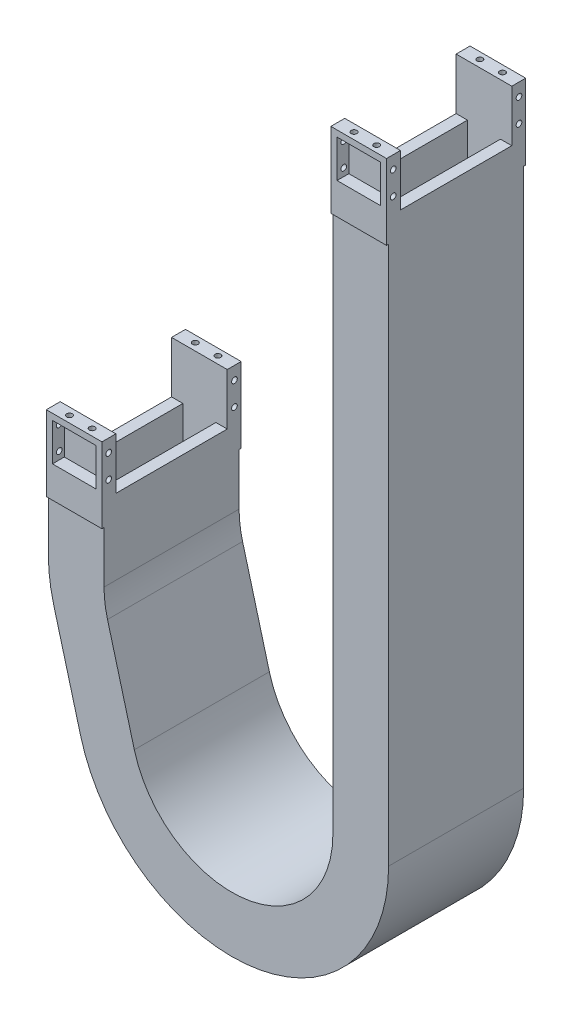
SolidWorks part; units mm, degrees
material "ABS"
ref_plane "Front Plane" through (0, 0, 0) normal (0, 0, 1) x (1, 0, 0)
ref_plane "Top Plane" through (0, 0, 0) normal (0, 1, 0) x (1, 0, 0)
ref_plane "Right Plane" through (0, 0, 0) normal (1, 0, 0) x (0, 0, -1)
ref_plane "Plane1" through (0, 300, 0) normal (0, 1, 0) x (-1, 0, 0)
sketch "Sketch1" plane through (0, 0, 0) normal (0, 0, 1) x (1, 0, 0)
  line L0 (-276, -375) -> (-276, -425)
  line L1 (0, -521.4286) -> (0, 0)
  line L2 (164.2548, 1) -> (-897.999, 1) construction
  line L3 (-245.6899, -553.9702) -> (-271.6899, -457.5416)
  line L4 (164.2548, 1) -> (164.2548, 204.572) construction
  line L5 (164.2548, 204.572) -> (-899.7452, 204.572) construction
  line L6 (164.2548, 204.572) -> (164.2548, 420.7437) construction
  line L7 (164.2548, 420.7437) -> (-507.0461, 420.7437) construction
  line L8 (164.2548, 204.572) -> (183.2548, 204.572) construction
  line L9 (164.2548, 420.7437) -> (164.2548, 572.9286) construction
  line L10 (164.2548, 572.9286) -> (-357.1738, 572.9286) construction
  line L11 (164.2548, 572.9286) -> (164.2548, 662.6262) construction
  line L12 (164.2548, 662.6262) -> (138.2548, 662.6262) construction
  line L13 (164.2548, 662.6262) -> (164.2548, 774.8796) construction
  line L14 (164.2548, 774.8796) -> (360.5557, 774.8796) construction
  arc A0 (-276, -425) -> (-271.6899, -457.5416) centre (-151, -425) ccw
  arc A1 (-245.6899, -553.9702) -> (0, -521.4286) centre (-125, -521.4286) ccw
  point P2 (-275, -99)
  dimension "D4" = 276
  dimension "D1" = 1
  dimension "D13" = 671.3009
  dimension "D6" = 125
  dimension "D2" = 275
  dimension "D3" = 100
  dimension "D5" = 1
  dimension "D7" = 521.4286
  dimension "D8" = 50
  dimension "D9" = 99.8723
  dimension "D10" = 1062.2538
  dimension "D11" = 1064
  dimension "D12" = 19
  dimension "D14" = 521.4286
  dimension "D15" = 26
  dimension "D16" = 196.3009
sketch "Sketch13" plane through (0, 0, 0) normal (0, 0, 1) x (1, 0, 0)
  line L0 (0, 228.6) -> (0, 203.2)
  line L1 (0, 228.6) -> (108, 228.6)
  line L2 (0, 203.2) -> (32, 203.2)
  line L3 (0, 177.8) -> (56, 177.8)
  line L4 (0, 152.4) -> (125, 152.4)
  line L5 (0, 127) -> (100, 127)
  line L6 (0, 101.6) -> (275, 101.6)
  line L7 (0, 76.2) -> (1, 76.2)
  line L8 (0, 50.8) -> (1, 50.8)
  line L9 (0, 25.4) -> (550, 25.4)
  line L10 (0, 203.2) -> (0, 177.8)
  line L11 (0, 177.8) -> (0, 152.4)
  line L12 (0, 152.4) -> (0, 127)
  line L13 (0, 127) -> (0, 101.6)
  line L14 (0, 101.6) -> (0, 76.2)
  line L15 (0, 76.2) -> (0, 50.8)
  line L16 (0, 50.8) -> (0, 25.4)
  line L17 (0, 25.4) -> (0, 0)
  line L18 (0, 228.6) -> (0, 254)
  line L19 (0, 254) -> (50, 254)
  line L20 (0, 254) -> (0, 279.4)
  line L21 (0, 279.4) -> (3, 279.4)
  dimension "D1" = 25.4
  dimension "D2" = 550
  dimension "D3" = 1
  dimension "D4" = 1
  dimension "D5" = 275
  dimension "D6" = 100
  dimension "D7" = 125
  dimension "D8" = 56
  dimension "D9" = 32
  dimension "D10" = 108
  dimension "D11" = 50
  dimension "D12" = 3
sketch "Sketch2" plane through (0, 0, 0) normal (0, 1, 0) x (1, 0, 0)
  line L0 (0, -11.5) -> (0, 0) construction
  line L1 (-27, 0) -> (27, 0)
  line L2 (-27, 0) -> (-27, -131)
  line L3 (-27, -131) -> (27, -131)
  line L4 (27, 0) -> (27, -131)
  line L5 (-16, -11.5) -> (16, -11.5)
  line L6 (-16, -11.5) -> (-16, -119.5)
  line L7 (-16, -119.5) -> (16, -119.5)
  line L8 (16, -11.5) -> (16, -119.5)
  line L9 (-27, -65.5) -> (-16, -65.5) construction
  dimension "D1" = 54
  dimension "D2" = 11.5
  dimension "D3" = 32
  dimension "D4" = 108
  dimension "D5" = 131
sweep "Sweep1" add profiles "Sketch2" path "Sketch1"
sketch "Sketch12" plane through (0, 0, 0) normal (0, 1, 0) x (1, 0, 0)
  line L0 (16, -11.5) -> (-16, -11.5) construction
  line L1 (-16, -11.5) -> (-16, -119.5) construction
  line L2 (16, -119.5) -> (16, -11.5) construction
  line L3 (-16, -119.5) -> (16, -119.5) construction
  line L4 (-27, 0) -> (-27, -131)
  line L5 (-27, -131) -> (27, -131)
  line L6 (27, -131) -> (27, 0)
  line L7 (27, 0) -> (-27, 0)
  line L8 (-27, 0) -> (-27, -131)
  line L9 (-27, -131) -> (27, -131)
  line L10 (27, -131) -> (27, 0)
  line L11 (27, 0) -> (-27, 0)
  line L12 (16, -11.5) -> (-16, -11.5)
  line L13 (-16, -11.5) -> (-16, -119.5)
  line L14 (16, -119.5) -> (16, -11.5)
  line L15 (-16, -119.5) -> (16, -119.5)
  dimension "D1" = 0
extrude "Boss-Extrude1" add sketch "Sketch12" along normal blind 1
sketch "Sketch3" plane through (0, 1, 0) normal (0, 1, 0) x (1, 0, 0)
  line L0 (27, -131) -> (27, 0) construction
  line L1 (-27, -133) -> (27, -133)
  line L2 (-27, -133) -> (-27, 2)
  line L3 (-27, 2) -> (27, 2)
  line L4 (27, -133) -> (27, 2)
  line L5 (-27, 0) -> (-27, -131) construction
  line L6 (-16, -65.5) -> (27, -65.5) construction
  line L7 (-16, -11.5) -> (-16, -119.5) construction
  line L9 (16, -11.5) -> (-16, -11.5) construction
  line L12 (16, -11.5) -> (-16, -11.5)
  line L13 (16, -119.5) -> (16, -11.5)
  line L14 (-16, -11.5) -> (-16, -119.5)
  line L15 (-16, -119.5) -> (16, -119.5)
  dimension "D1" = 13.5
extrude "Extrude1" add sketch "Sketch3" along normal blind 73
sketch "Sketch4" plane through (27, 0, 0) normal (1, 0, 0) x (0, 0, -1)
  line L0 (2, 74) -> (-133, 74) construction
  line L1 (-119.5, 74) -> (-11.5, 74)
  line L2 (-119.5, 74) -> (-119.5, 24)
  line L3 (-119.5, 24) -> (-11.5, 24)
  line L4 (-11.5, 74) -> (-11.5, 24)
  line L5 (-11.5, -521.4286) -> (-11.5, 74) construction
  line L6 (-119.5, -521.4286) -> (-119.5, 74) construction
  line L7 (-65.5, 61.5) -> (-65.5, 74) construction
  line L8 (-126.5, 61.5) -> (-4.5, 61.5) construction
  line L9 (-126.5, 61.5) -> (-126.5, 39) construction
  line L10 (-126.5, 39) -> (-4.5, 39) construction
  line L11 (-4.5, 61.5) -> (-4.5, 39) construction
  circle A0 centre (-126.5, 61.5) radius 2.75
  circle A1 centre (-126.5, 39) radius 2.75
  circle A2 centre (-4.5, 39) radius 2.75
  circle A3 centre (-4.5, 61.5) radius 2.75
  dimension "D2" = 5.5
  dimension "D1" = 50
  dimension "D3" = 14
  dimension "D4" = 12.5
  dimension "D5" = 22.5
extrude "Extrude2" cut sketch "Sketch4" against normal up to surface (54 mm away) up to face at (-27, -176.6607, 65.25)
sketch "Sketch7" plane through (0, -375, 0) normal (0, 1, 0) x (1, 0, 0)
  line L1 (-303, -133) -> (-249, -133)
  line L2 (-303, -133) -> (-303, 2)
  line L3 (-303, 2) -> (-249, 2)
  line L4 (-249, -133) -> (-249, 2)
  line L8 (-260, -11.5) -> (-292, -11.5)
  line L9 (-292, -11.5) -> (-292, -119.5)
  line L10 (-292, -119.5) -> (-260, -119.5)
  line L11 (-260, -119.5) -> (-260, -11.5)
  line L12 (-260, -65.5) -> (-249, -65.5) construction
  line L15 (-249, 0) -> (-249, -131) construction
  line L16 (-303, -131) -> (-303, 0) construction
  dimension "D1" = 13.5
extrude "Extrude5" add sketch "Sketch7" along normal blind 73
sketch "Sketch8" plane through (-249, 0, 0) normal (1, 0, 0) x (0, 0, -1)
  line L0 (2, -302) -> (-133, -302) construction
  line L1 (-119.5, -302) -> (-11.5, -302)
  line L2 (-119.5, -302) -> (-119.5, -352)
  line L3 (-119.5, -352) -> (-11.5, -352)
  line L4 (-11.5, -302) -> (-11.5, -352)
  line L5 (-65.5, -314.5) -> (-65.5, -302) construction
  line L6 (-126.5, -337) -> (-4.5, -337) construction
  line L7 (-126.5, -337) -> (-126.5, -314.5) construction
  line L8 (-126.5, -314.5) -> (-4.5, -314.5) construction
  line L9 (-4.5, -337) -> (-4.5, -314.5) construction
  line L10 (-119.5, -425) -> (-119.5, -302) construction
  line L11 (-11.5, -425) -> (-11.5, -302) construction
  circle A0 centre (-4.5, -337) radius 2.75
  circle A1 centre (-4.5, -314.5) radius 2.75
  circle A2 centre (-126.5, -337) radius 2.75
  circle A3 centre (-126.5, -314.5) radius 2.75
  dimension "D5" = 5.5
  dimension "D1" = 7
  dimension "D2" = 12.5
  dimension "D3" = 22.5
  dimension "D4" = 50
extrude "Extrude6" cut sketch "Sketch8" against normal up to surface (54 mm away) up to face at (-303, -369.25, 65.5)
sketch "Sketch5" plane through (0, 0, 133) normal (0, 0, 1) x (1, 0, 0)
  line L1 (21, 68) -> (-21, 68)
  line L2 (21, 68) -> (21, 31.5)
  line L3 (21, 31.5) -> (-21, 31.5)
  line L4 (-21, 68) -> (-21, 31.5)
  line L6 (27, 74) -> (-27, 74) construction
  line L7 (-303, -302) -> (-303, -375) construction
  line L8 (-297, -308) -> (-255, -308)
  line L9 (-297, -308) -> (-297, -344.5)
  line L10 (-297, -344.5) -> (-255, -344.5)
  line L11 (-255, -308) -> (-255, -344.5)
  line L12 (-249, -302) -> (-249, -375) construction
  line L13 (-249, -302) -> (-303, -302) construction
  line L14 (27, 74) -> (27, 1) construction
  line L15 (-27, 74) -> (-27, 1) construction
  dimension "D1" = 6
  dimension "D2" = 6
  dimension "D3" = 6
  dimension "D4" = 42.5
  dimension "D5" = 6
  dimension "D6" = 6
  dimension "D7" = 6
  dimension "D8" = 42.5
extrude "Extrude3" cut sketch "Sketch5" against normal blind 11.5
sketch "Sketch6" plane through (0, 0, -2) normal (0, 0, -1) x (-1, 0, 0)
  line L4 (-21, 68) -> (-21, 31.5)
  line L5 (-21, 31.5) -> (21, 31.5)
  line L6 (-21, 68) -> (-21, 31.5)
  line L7 (21, 68) -> (-21, 68)
  line L8 (21, 31.5) -> (21, 68)
  line L9 (-21, 31.5) -> (21, 31.5)
  line L10 (21, 31.5) -> (21, 68)
  line L11 (21, 68) -> (-21, 68)
  line L12 (297, -344.5) -> (297, -308)
  line L13 (255, -344.5) -> (297, -344.5)
  line L14 (255, -308) -> (255, -344.5)
  line L15 (297, -308) -> (255, -308)
  line L16 (297, -344.5) -> (297, -308)
  line L17 (255, -344.5) -> (297, -344.5)
  line L18 (255, -308) -> (255, -344.5)
  line L19 (297, -308) -> (255, -308)
  dimension "D1" = 0
  dimension "D2" = 0
extrude "Extrude4" cut sketch "Sketch6" against normal blind 11.5
sketch "Sketch9" plane through (0, 74, 0) normal (0, 1, 0) x (1, 0, 0)
  line L0 (27, -119.5) -> (-27, -119.5) construction
  line L1 (-11, -126.5) -> (11, -126.5) construction
  line L2 (-11, -126.5) -> (-11, -4.5) construction
  line L3 (-11, -4.5) -> (11, -4.5) construction
  line L4 (11, -126.5) -> (11, -4.5) construction
  line L5 (-27, -11.5) -> (-27, -119.5) construction
  line L6 (-27, -11.5) -> (-27, -119.5) construction
  line L7 (27, -119.5) -> (-27, -119.5) construction
  line L8 (0, -126.5) -> (0, -119.5) construction
  line L9 (11, -65.5) -> (-27, -65.5) construction
  circle A0 centre (-11, -126.5) radius 2.75
  circle A1 centre (11, -126.5) radius 2.75
  circle A2 centre (11, -4.5) radius 2.75
  circle A3 centre (-11, -4.5) radius 2.75
  dimension "D1" = 5.5
  dimension "D2" = 22
  dimension "D3" = 7
extrude "Extrude7" cut sketch "Sketch9" against normal blind 7
sketch "Sketch10" plane through (0, -302, 0) normal (0, 1, 0) x (1, 0, 0)
  line L0 (-249, -119.5) -> (-303, -119.5) construction
  line L1 (-287, -126.5) -> (-265, -126.5) construction
  line L2 (-287, -126.5) -> (-287, -4.5) construction
  line L3 (-287, -4.5) -> (-265, -4.5) construction
  line L4 (-265, -126.5) -> (-265, -4.5) construction
  line L5 (-303, -11.5) -> (-303, -119.5) construction
  line L6 (-249, -119.5) -> (-303, -119.5) construction
  line L7 (-303, -11.5) -> (-303, -119.5) construction
  line L8 (-276, -119.5) -> (-276, -126.5) construction
  line L9 (-303, -65.5) -> (-265, -65.5) construction
  circle A0 centre (-287, -126.5) radius 2.75
  circle A1 centre (-265, -126.5) radius 2.75
  circle A2 centre (-287, -4.5) radius 2.75
  circle A3 centre (-265, -4.5) radius 2.75
  dimension "D1" = 5.5
  dimension "D2" = 22
  dimension "D3" = 7
extrude "Extrude8" cut sketch "Sketch10" against normal blind 7
other "Freeze***"
